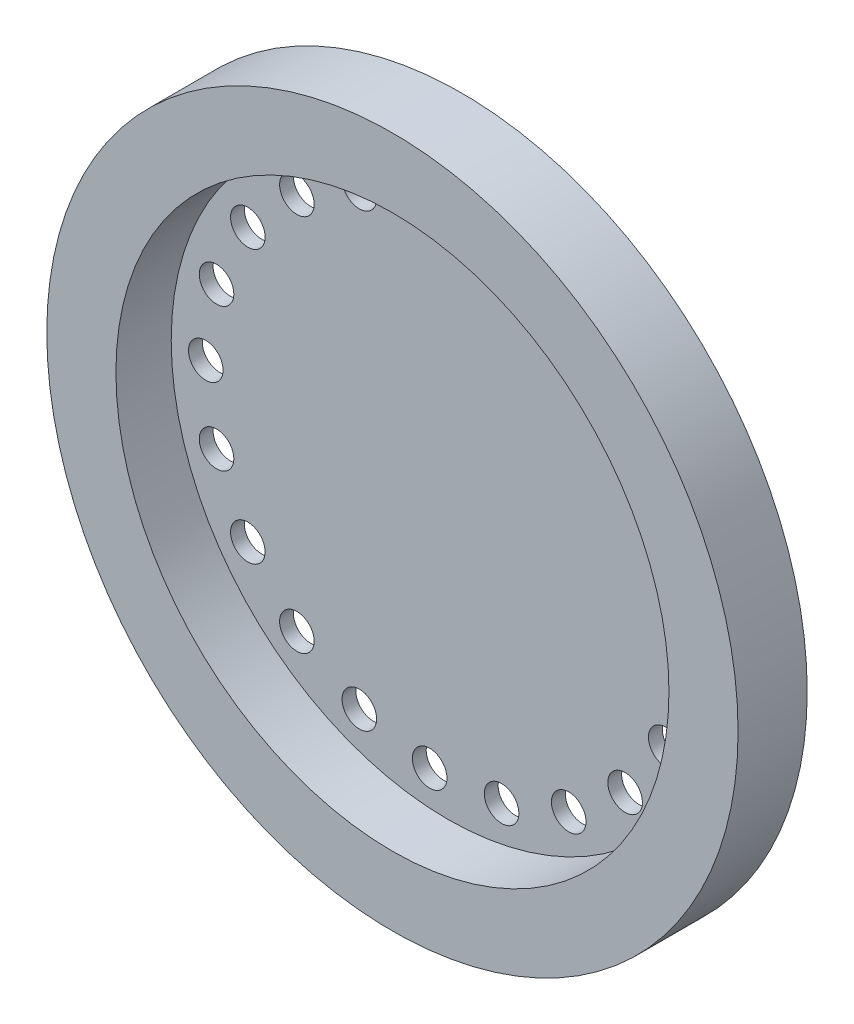
SolidWorks part; units mm, degrees
ref_plane "Front Plane" through (0, 0, 0) normal (0, 0, 1) x (1, 0, 0)
ref_plane "Top Plane" through (0, 0, 0) normal (0, 1, 0) x (1, 0, 0)
ref_plane "Right Plane" through (0, 0, 0) normal (1, 0, 0) x (0, 0, -1)
sketch "Sketch1" plane through (0, 0, 0) normal (0, 0, 1) x (1, 0, 0)
  line L0 (0, 0) -> (-44.45, 0) construction
  circle A0 centre (0, 0) radius 50.8
  circle A1 centre (-44.45, 0) radius 3.175
  circle A2 centre (-42.4752, 13.1019) radius 3.175
  circle A3 centre (-36.7263, 25.0396) radius 3.175
  circle A4 centre (-27.7141, 34.7524) radius 3.175
  circle A5 centre (-16.2394, 41.3773) radius 3.175
  circle A6 centre (-3.3218, 44.3257) radius 3.175
  circle A7 centre (9.8911, 43.3355) radius 3.175
  circle A8 centre (22.225, 38.4948) radius 3.175
  circle A9 centre (32.5842, 30.2337) radius 3.175
  circle A10 centre (40.0481, 19.2861) radius 3.175
  circle A11 centre (43.9535, 6.6249) radius 3.175
  circle A12 centre (43.9535, -6.6249) radius 3.175
  circle A13 centre (40.0481, -19.2861) radius 3.175
  circle A14 centre (32.5842, -30.2337) radius 3.175
  circle A15 centre (22.225, -38.4948) radius 3.175
  circle A16 centre (9.8911, -43.3355) radius 3.175
  circle A17 centre (-3.3218, -44.3257) radius 3.175
  circle A18 centre (-16.2394, -41.3773) radius 3.175
  circle A19 centre (-27.7141, -34.7524) radius 3.175
  circle A20 centre (-36.7263, -25.0396) radius 3.175
  circle A21 centre (-42.4752, -13.1019) radius 3.175
  point P3 (-50.8, 0)
  point P4 (0, 0)
  point P5 (-44.45, 0)
  dimension "D1" = 101.6
  dimension "D3" = 6.35
  dimension "D2" = 6.35
  dimension "D5" = 44.45
  dimension "D6" = 44.45
  dimension "D4" = 21
sketch "Sketch4" plane through (0, 0, 0) normal (0, 0, 1) x (1, 0, 0)
  circle A0 centre (0, 0) radius 63.5
  circle A1 centre (0, 0) radius 50.8
  dimension "D1" = 127
  dimension "D2" = 101.6
extrude "Boss-Extrude4" add sketch "Sketch4" along normal blind 12.7
extrude "Boss-Extrude5" add sketch "Sketch1" along normal blind 2.54
